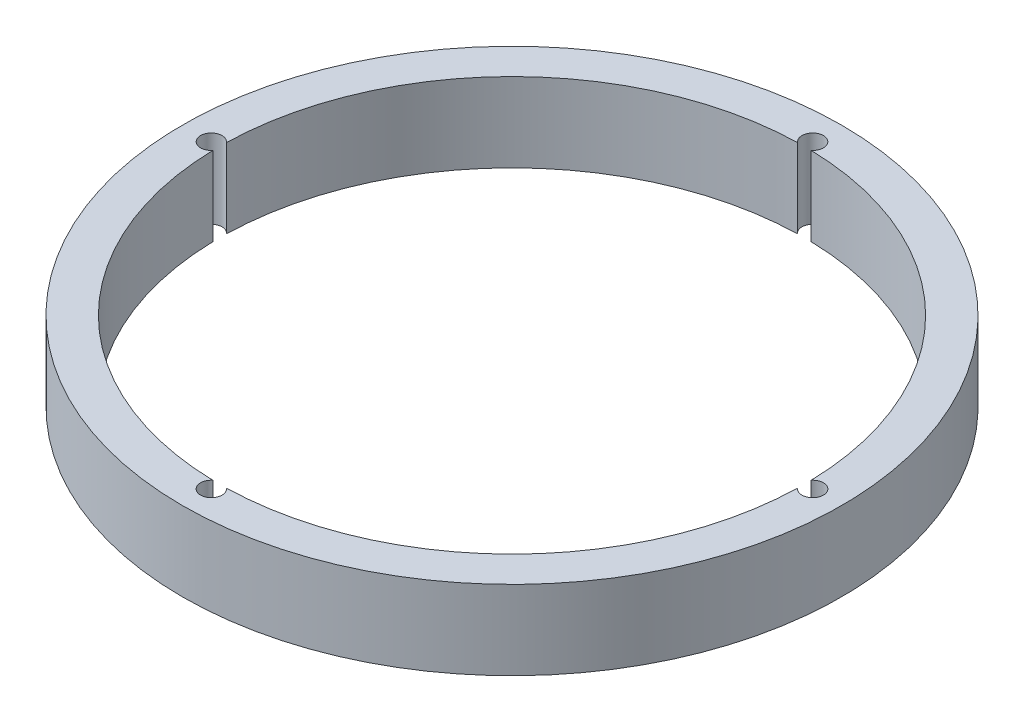
SolidWorks part; units mm, degrees
ref_plane "Front Plane" through (0, 0, 0) normal (0, 0, 1) x (1, 0, 0)
ref_plane "Top Plane" through (0, 0, 0) normal (0, 1, 0) x (1, 0, 0)
ref_plane "Right Plane" through (0, 0, 0) normal (1, 0, 0) x (0, 0, -1)
sketch "Sketch1" plane through (0, 0, 0) normal (0, 1, 0) x (1, 0, 0)
  line L0 (0, 0) -> (0, 73) construction
  line L1 (0, 0) -> (73, 0) construction
  line L2 (0, 0) -> (0, -73) construction
  line L3 (0, 0) -> (-73, 0) construction
  circle A0 centre (0, 0) radius 80
  arc A1 (1.6383, 70.9811) -> (-1.6383, 70.9811) centre (0, 73) ccw
  arc A2 (70.9811, -1.6383) -> (70.9811, 1.6383) centre (73, 0) ccw
  arc A3 (-1.6383, -70.9811) -> (1.6383, -70.9811) centre (0, -73) ccw
  arc A4 (-70.9811, 1.6383) -> (-70.9811, -1.6383) centre (-73, 0) ccw
  arc A5 (-70.9811, -1.6383) -> (-1.6383, -70.9811) centre (0, 0) ccw
  arc A6 (-1.6383, 70.9811) -> (-70.9811, 1.6383) centre (0, 0) ccw
  arc A7 (70.9811, 1.6383) -> (1.6383, 70.9811) centre (0, 0) ccw
  arc A8 (1.6383, -70.9811) -> (70.9811, -1.6383) centre (0, 0) ccw
  point P14 (0, 0)
  dimension "D1" = 160
  dimension "D2" = 5.2
  dimension "D5" = 142
  dimension "D3" = 73
  dimension "D4" = 4
extrude "Boss-Extrude1" add sketch "Sketch1" along normal blind 19.2
